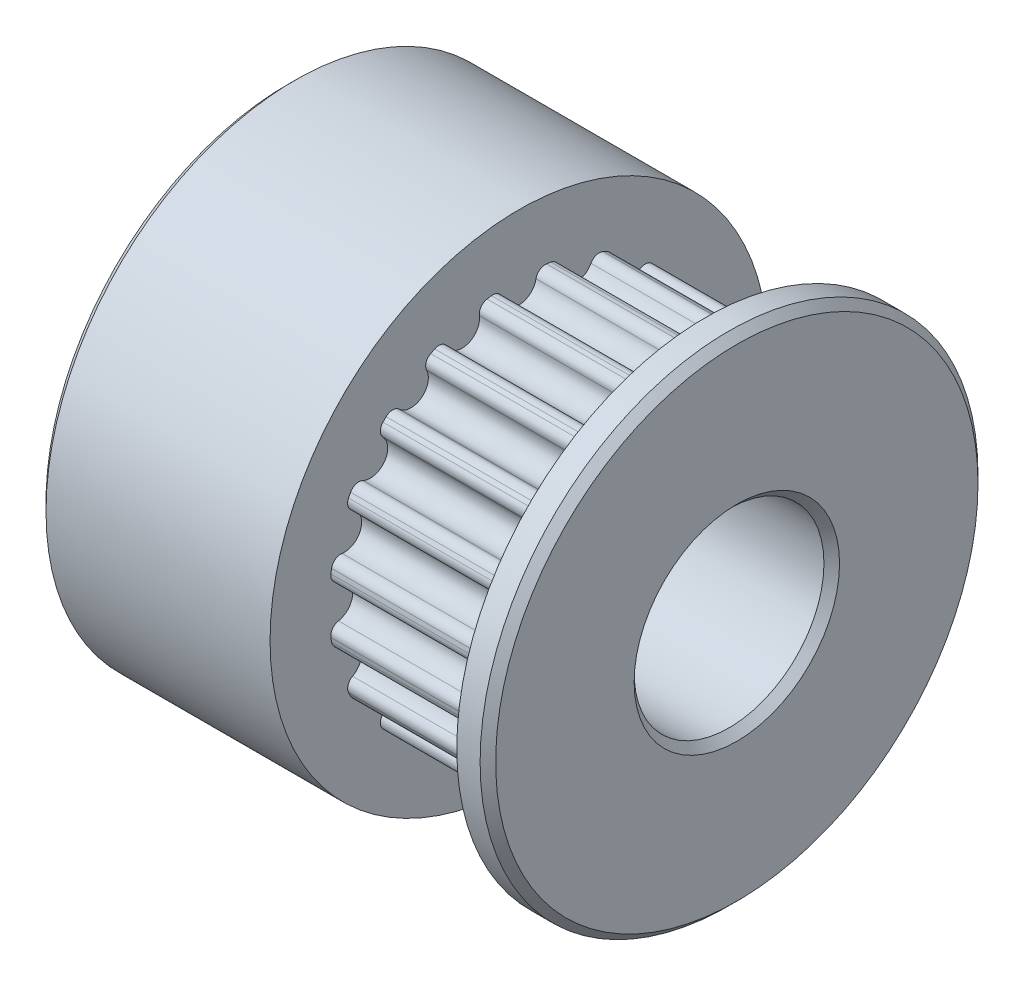
SolidWorks part; units mm, degrees
ref_plane "Front Plane" through (0, 0, 0) normal (0, 0, 1) x (1, 0, 0)
ref_plane "Top Plane" through (0, 0, 0) normal (0, 1, 0) x (1, 0, 0)
ref_plane "Right Plane" through (0, 0, 0) normal (1, 0, 0) x (0, 0, -1)
sketch "Sketch1" plane through (0, 0, 0) normal (1, 0, 0) x (0, 0, -1)
  line L0 (-8.0027, 0.002) -> (7.9973, 0.002) construction
  line L1 (-0.5912, -5.3455) -> (0.627, -5.3455) construction
  line L2 (0, 0) -> (0, -10.4547) construction
  line L3 (-0.6734, -6.11) -> (-0.514, -6.11) construction
  line L4 (0.514, -6.11) -> (0.627, -6.11) construction
  circle A0 centre (0, 0) radius 8 construction
  arc A1 (0.5225, -6.0876) -> (1.3842, -5.9511) centre (0, 0) ccw
  arc A2 (0.5225, -6.0876) -> (-0.5225, -6.0876) centre (0, -5.9005) ccw
  arc A3 (-1.3842, -5.9511) -> (-2.3781, -5.6282) centre (-1.8234, -5.6117) ccw
  arc A4 (-3.1555, -5.2321) -> (-4.0009, -4.6179) centre (-3.4682, -4.7736) ccw
  arc A5 (-4.6179, -4.0009) -> (-5.2321, -3.1555) centre (-4.7736, -3.4682) ccw
  arc A6 (-5.6282, -2.3781) -> (-5.9511, -1.3842) centre (-5.6117, -1.8234) ccw
  arc A7 (-6.0876, -0.5225) -> (-6.0876, 0.5225) centre (-5.9005, 0) ccw
  arc A8 (-5.9511, 1.3842) -> (-5.6282, 2.3781) centre (-5.6117, 1.8234) ccw
  arc A9 (-5.2321, 3.1555) -> (-4.6179, 4.0009) centre (-4.7736, 3.4682) ccw
  arc A10 (-4.0009, 4.6179) -> (-3.1555, 5.2321) centre (-3.4682, 4.7736) ccw
  arc A11 (-2.3781, 5.6282) -> (-1.3842, 5.9511) centre (-1.8234, 5.6117) ccw
  arc A12 (-0.5225, 6.0876) -> (0.5225, 6.0876) centre (0, 5.9005) ccw
  arc A13 (1.3842, 5.9511) -> (2.3781, 5.6282) centre (1.8234, 5.6117) ccw
  arc A14 (3.1555, 5.2321) -> (4.0009, 4.6179) centre (3.4682, 4.7736) ccw
  arc A15 (4.6179, 4.0009) -> (5.2321, 3.1555) centre (4.7736, 3.4682) ccw
  arc A16 (5.6282, 2.3781) -> (5.9511, 1.3842) centre (5.6117, 1.8234) ccw
  arc A17 (6.0876, 0.5225) -> (6.0876, -0.5225) centre (5.9005, 0) ccw
  arc A18 (5.9511, -1.3842) -> (5.6282, -2.3781) centre (5.6117, -1.8234) ccw
  arc A19 (5.2321, -3.1555) -> (4.6179, -4.0009) centre (4.7736, -3.4682) ccw
  arc A20 (4.0009, -4.6179) -> (3.1555, -5.2321) centre (3.4682, -4.7736) ccw
  arc A21 (2.3781, -5.6282) -> (1.3842, -5.9511) centre (1.8234, -5.6117) ccw
  arc A22 (-1.3842, -5.9511) -> (-0.5225, -6.0876) centre (0, 0) ccw
  arc A23 (-3.1555, -5.2321) -> (-2.3781, -5.6282) centre (0, 0) ccw
  arc A24 (2.3781, -5.6282) -> (3.1555, -5.2321) centre (0, 0) ccw
  arc A25 (4.0009, -4.6179) -> (4.6179, -4.0009) centre (0, 0) ccw
  arc A26 (5.2321, -3.1555) -> (5.6282, -2.3781) centre (0, 0) ccw
  arc A27 (5.9511, -1.3842) -> (6.0876, -0.5225) centre (0, 0) ccw
  arc A28 (6.0876, 0.5225) -> (5.9511, 1.3842) centre (0, 0) ccw
  arc A29 (5.6282, 2.3781) -> (5.2321, 3.1555) centre (0, 0) ccw
  arc A30 (4.6179, 4.0009) -> (4.0009, 4.6179) centre (0, 0) ccw
  arc A31 (3.1555, 5.2321) -> (2.3781, 5.6282) centre (0, 0) ccw
  arc A32 (1.3842, 5.9511) -> (0.5225, 6.0876) centre (0, 0) ccw
  arc A33 (-0.5225, 6.0876) -> (-1.3842, 5.9511) centre (0, 0) ccw
  arc A34 (-2.3781, 5.6282) -> (-3.1555, 5.2321) centre (0, 0) ccw
  arc A35 (-4.0009, 4.6179) -> (-4.6179, 4.0009) centre (0, 0) ccw
  arc A36 (-5.2321, 3.1555) -> (-5.6282, 2.3781) centre (0, 0) ccw
  arc A37 (-5.9511, 1.3842) -> (-6.0876, 0.5225) centre (0, 0) ccw
  arc A38 (-6.0876, -0.5225) -> (-5.9511, -1.3842) centre (0, 0) ccw
  arc A39 (-5.6282, -2.3781) -> (-5.2321, -3.1555) centre (0, 0) ccw
  arc A40 (-4.6179, -4.0009) -> (-4.0009, -4.6179) centre (0, 0) ccw
  point P74 (0, 0)
  dimension "D2" = 16
  dimension "D3" = 12.22
  dimension "D4" = 1.11
  dimension "D1" = 16
  dimension "D5" = 20
extrude "Boss-Extrude1" add sketch "Sketch1" along normal blind 6
fillet "Fillet1" radius 0.3 40 edges at (3, -0.5225, 6.0876) (3, -2.3781, 5.6282) (3, -4.0009, 4.6179) (3, -5.2321, 3.1555) (3, -5.9511, 1.3842) (3, -6.0876, -0.5225) (3, -5.6282, -2.3781) (3, -4.6179, -4.0009) (3, -3.1555, -5.2321) (3, -1.3842, -5.9511) (3, 0.5225, -6.0876) (3, 2.3781, -5.6282) (3, 4.0009, -4.6179) (3, 5.2321, -3.1555) (3, 5.9511, -1.3842) (3, 5.6282, 2.3781) (3, 4.6179, 4.0009) (3, 3.1555, 5.2321) (3, 1.3842, 5.9511) (3, 2.3781, 5.6282) (3, 0.5225, 6.0876) (3, -1.3842, 5.9511) (3, -3.1555, 5.2321) (3, -4.6179, 4.0009) (3, -5.6282, 2.3781) (3, -6.0876, 0.5225) (3, -5.9511, -1.3842) (3, -5.2321, -3.1555) (3, -4.0009, -4.6179) (3, -2.3781, -5.6282) (3, -0.5225, -6.0876) (3, 1.3842, -5.9511) (3, 3.1555, -5.2321) (3, 4.6179, -4.0009) (3, 5.6282, -2.3781) (3, 6.0876, -0.5225) (3, 5.9511, 1.3842) (3, 5.2321, 3.1555) (3, 4.0009, 4.6179) (3, 6.0876, 0.5225)
sketch "Sketch2" plane through (0, 0, 0) normal (1, 0, 0) x (0, 0, -1)
  circle A0 centre (0, 0) radius 8
  dimension "D1" = 16
extrude "Boss-Extrude2" add sketch "Sketch2" against normal blind 7.45
sketch "Sketch3" plane through (6, 0, 0) normal (1, 0, 0) x (0, 0, -1)
  circle A0 centre (0, 0) radius 8 construction
  circle A1 centre (0, 0) radius 8
extrude "Boss-Extrude3" add sketch "Sketch3" along normal blind 1
sketch "Sketch4" plane through (0, 0, 0) normal (1, 0, 0) x (0, 0, -1)
  circle A0 centre (0, 0) radius 3.05
  dimension "D1" = 6.1
extrude "Cut-Extrude1" cut sketch "Sketch4" against normal through all both and the other way through all
chamfer "Chamfer1" distance 0.25 angle 45 4 edges at (-7.45, 0, -8) (-7.45, 0, -3.05) (7, 0, -8) (7, 0, -3.05)
sketch "Sketch5" plane through (0, 0, 0) normal (0, 0, 1) x (1, 0, 0)
  line L0 (-7.45, 7.75) -> (-7.45, -7.75) construction
  circle A0 centre (-3.45, 0) radius 1.75
  dimension "D1" = 3.5
  dimension "D2" = 4
extrude "Cut-Extrude2" cut sketch "Sketch5" against normal through all
ref_plane "Plane2" through (-7.2, 0, 0) normal (1, 0, 0) x (0, 0, -1)
sketch "Sketch8" plane through (-7.2, 0, 0) normal (1, 0, 0) x (0, 0, -1)
  line L0 (-2.227, 3.05) -> (2.6592, 3.05) construction
  line L1 (-1.7471, -2.5) -> (1.7471, -2.5)
  circle A0 centre (0, 0) radius 3.05 construction
  arc A1 (-1.7471, -2.5) -> (1.7471, -2.5) centre (0, 0) ccw
  dimension "D1" = 5.55
sketch "Sketch6" plane through (0, 0, 0) normal (0, 1, 0) x (1, 0, 0)
  line L0 (-7.45, 7.75) -> (-7.45, -7.75) construction
  circle A0 centre (-3.45, 0) radius 1.75
  dimension "D1" = 3.5
  dimension "D2" = 4
extrude "Cut-Extrude3" cut sketch "Sketch6" against normal through all
ref_plane "Plane3" through (0, -10, 0) normal (0, 1, 0) x (1, 0, 0)
sketch "Sketch9" plane through (0, -10, 0) normal (0, 1, 0) x (1, 0, 0)
  circle A0 centre (-3.45, 0) radius 1.75 construction
  circle A1 centre (-3.45, 0) radius 1.75
ref_plane "Plane4" through (-3.45, 0, 0) normal (-1, 0, 0) x (0, 0, 1)
sketch "Sketch10" plane through (-3.45, 0, 0) normal (-1, 0, 0) x (0, 0, 1)
  line L0 (0, -10) -> (0, 0) construction
  line L1 (1.75, -10) -> (-1.75, -10) construction
